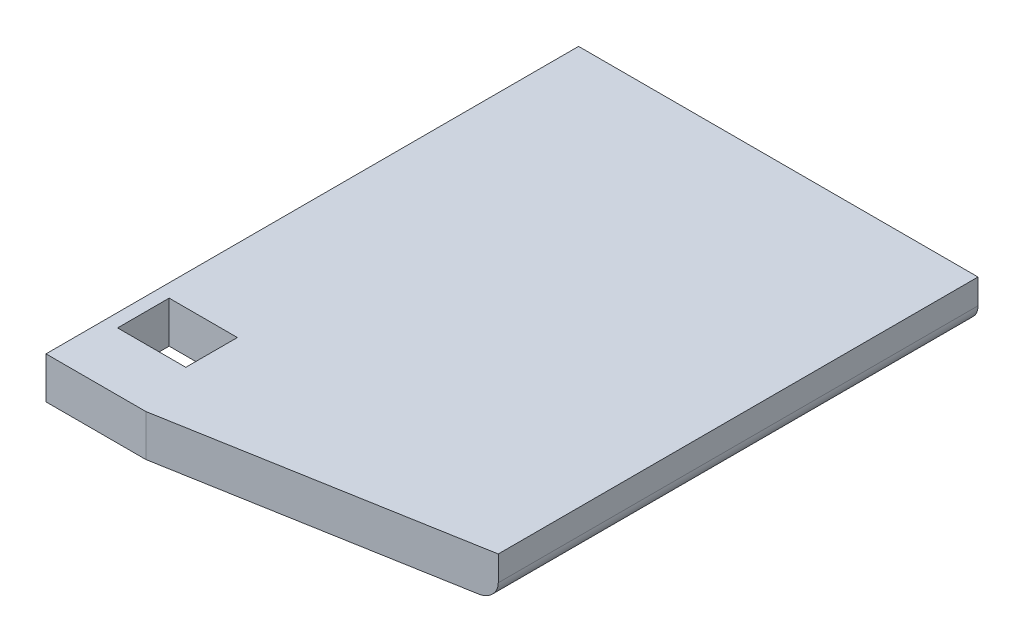
SolidWorks part; units mm, degrees
ref_plane "前视基准面" through (0, 0, 0) normal (1, 0, 0) x (0, 1, 0)
ref_plane "上视基准面" through (0, 0, 0) normal (0, 0, 1) x (0, 1, 0)
ref_plane "右视基准面" through (0, 0, 0) normal (0, 1, 0) x (-1, 0, 0)
other "Configuration Table"
sketch "草图3" plane through (0, 0, 0) normal (0, 0, 1) x (0, 1, 0)
  line L1 (0, 0) -> (2.5, 0)
  line L2 (0, 0) -> (0, -24)
  line L3 (0, -24) -> (2.5, -24)
  line L4 (2.5, 0) -> (2.5, -24)
  line L5 (0, 0) -> (2.5, -24) construction
  line L6 (0, -24) -> (2.5, 0) construction
  point P4 (1.25, -12)
  dimension "D1" = 2.5
  dimension "D2" = 24
extrude "凸台-拉伸1" add sketch "草图3" along normal blind 33
fillet "圆角1" radius 1 1 edges at (24, 0, 16.5)
sketch "草图5" plane through (0, 2.5, 0) normal (0, 1, 0) x (-1, 0, 0)
  line L0 (-3, 33) -> (-3, 0) construction
  line L1 (-24, 33) -> (0, 33) construction
  line L2 (-24, 0) -> (0, 0) construction
  line L3 (0, 33) -> (0, 0) construction
  line L4 (-3, 33) -> (-24, 31.1627)
  line L5 (-24, 33) -> (-24, 0) construction
  line L6 (-24, 31.1627) -> (-24, 33)
  line L7 (-24, 33) -> (-3, 33)
  dimension "D1" = 3
  dimension "D2" = 5
extrude "切除-拉伸3" cut sketch "草图5" against normal through all
sketch "草图6" plane through (0, 0, 0) normal (-1, 0, 0) x (0, -1, 0)
  line L0 (-2.5, 33) -> (-2.5, 0) construction
  line L1 (-2.5, 28.5) -> (0, 28.5)
  line L2 (-2.5, 28.5) -> (-2.5, 25.4)
  line L3 (-2.5, 25.4) -> (0, 25.4)
  line L4 (0, 28.5) -> (0, 25.4)
  line L5 (-2.5, 28.5) -> (0, 25.4) construction
  line L6 (-2.5, 25.4) -> (0, 28.5) construction
  line L7 (0, 33) -> (0, 0) construction
  line L8 (-2.5, 33) -> (0, 33) construction
  point P4 (-1.25, 26.95)
  dimension "D1" = 4.5
  dimension "D2" = 3.1
extrude "切除-拉伸4" cut sketch "草图6" against normal blind 4.9
sketch "草图7" plane through (0, 0, 33) normal (0, 0, 1) x (1, 0, 0)
  line L1 (24, 2.5) -> (0, 2.5)
  line L2 (24, 2.5) -> (24, 0)
  line L3 (24, 0) -> (0, 0)
  line L4 (0, 2.5) -> (0, 0)
  line L5 (24, 2.5) -> (0, 0) construction
  line L6 (24, 0) -> (0, 2.5) construction
  point P4 (12, 1.25)
extrude "切除-拉伸5" cut sketch "草图7" against normal blind 1
sketch "草图8" plane through (0, 2.5, 0) normal (0, 1, 0) x (-1, 0, 0)
  line L0 (-24, 31.1627) -> (-24, 0) construction
  line L1 (-14.4301, 32) -> (0, 32) construction
  line L2 (-24, 31.1627) -> (-14.4301, 32) construction
  line L3 (-24, 31.1627) -> (-24, 28.8261)
  line L4 (-14.4301, 32) -> (-6, 32)
  line L5 (-24, 31.1627) -> (-14.4301, 32)
  line L6 (-24, 28.8261) -> (-6, 32)
  line L7 (0, 32) -> (0, 28.5) construction
  dimension "D1" = 6
  dimension "D2" = 14.4301
  dimension "D3" = 10
extrude "切除-拉伸6" cut sketch "草图8" against normal through all
sketch "草图9" plane through (0, 0, 0) normal (0, -1, 0) x (1, 0, 0)
  line L0 (1, 32.8816) -> (1, 0) construction
  line L1 (23, 29.0024) -> (6, 32) construction
  line L2 (0, 0) -> (23, 0) construction
  line L3 (22, 29.1788) -> (22, 0) construction
  line L4 (1, 10) -> (22, 10) construction
  line L5 (0, 25.4) -> (0, 0) construction
  line L6 (24, 28.8261) -> (24, 0) construction
  line L7 (23, 0) -> (23, 29.0024) construction
  text T0 "V10" font "汉仪长仿宋体" height in points 26
  dimension "D1" = 1
  dimension "D2" = 2
  dimension "D3" = 10
  dimension "D4" = 1
extrude "切除-拉伸7" cut sketch "草图9" against normal blind 1
sketch "磁铁宽度挡板" plane through (0, 0, 0) normal (0, -1, 0) x (1, 0, 0)
  line L0 (4.9, 25.4) -> (0, 25.4) construction
  line L1 (0, 28.5) -> (0.8, 28.5)
  line L2 (0, 28.5) -> (0, 25.4)
  line L3 (0, 25.4) -> (0.8, 25.4)
  line L4 (0.8, 28.5) -> (0.8, 25.4)
  line L5 (0, 28.5) -> (0.8, 25.4) construction
  line L6 (0, 25.4) -> (0.8, 28.5) construction
  line L7 (4.9, 25.4) -> (4.9, 28.5) construction
  line L8 (4.9, 28.5) -> (0, 28.5) construction
  point P4 (0.4, 26.95)
  dimension "D1" = 4.1
  dimension "D2" = 0.8
  dimension "D3" = 3.1
extrude "凸台-拉伸2" add sketch "磁铁宽度挡板" against normal up to surface (2.5 mm away) up to face at (7.0889, 2.5, 22.2918)
